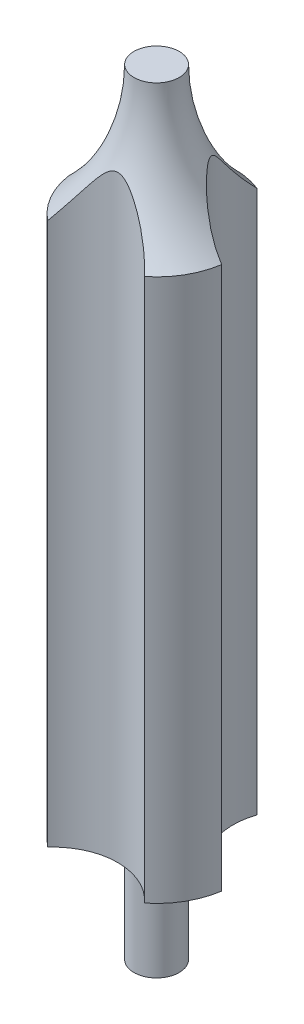
SolidWorks part; units mm, degrees
ref_plane "Спереди" through (0, 0, 0) normal (0, 0, 1) x (1, 0, 0)
ref_plane "Сверху" through (0, 0, 0) normal (0, 1, 0) x (1, 0, 0)
ref_plane "Справа" through (0, 0, 0) normal (1, 0, 0) x (0, 0, -1)
sketch "Эскиз1" plane through (0, 0, 0) normal (0, 0, 1) x (1, 0, 0)
  line L0 (0, 18.1736) -> (0, -11.8264)
  line L1 (0, 18.1736) -> (-0.875, 18.1736)
  line L2 (-3, 13.1736) -> (0, 13.1736)
  line L3 (-3, 13.1736) -> (-3, -7.8264)
  line L4 (-3, -7.8264) -> (-0.875, -7.8264)
  line L5 (-0.875, -7.8264) -> (-0.875, -11.8264)
  line L6 (-0.875, -11.8264) -> (0, -11.8264)
  arc A1 (-3, 13.1736) -> (-0.875, 18.1736) centre (-7.875, 18.1971) ccw
  point P8 (0, -11.7055)
  point P12 (0, 0)
  point P14 (-0.875, 18.1325)
  dimension "D2" = 26
  dimension "D5" = 7
  dimension "D1" = 0.875
  dimension "D3" = 5
  dimension "D4" = 3
  dimension "D6" = 30
revolve "Повернуть1" add sketch "Эскиз1" angle 360 about L0
sketch "Эскиз2" plane through (0, 18.1736, 0) normal (0, 1, 0) x (1, 0, 0)
  line L0 (0, -4) -> (0, 0) construction
  line L1 (0, 0) -> (-3.4641, 2) construction
  line L2 (3.4641, 2) -> (0, 0) construction
  circle A0 centre (-3.4641, 2) radius 2.5
  circle A1 centre (3.4641, 2) radius 2.5
  circle A2 centre (0, -4) radius 2.5
  circle A3 centre (0, 0) radius 1.5
  point P6 (-1.299, 0.75)
  point P9 (1.299, 0.75)
  point P10 (0, -1.5)
  point P12 (0, 0)
  point P13 (0, 0)
  dimension "D3" = 5
  dimension "D4" = 5
  dimension "D5" = 5
  dimension "D6" = 3
  dimension "D1" = 120
  dimension "D2" = 120
extrude "Вырез-Вытянуть1" cut sketch "Эскиз2" against normal through all both and the other way through all contours A0 | A1 | A2
sketch "Эскиз3" plane through (0, -11.8264, 0) normal (0, -1, 0) x (1, 0, 0)
  circle A0 centre (0, 0) radius 0.5
  dimension "D1" = 1
extrude "Вырез-Вытянуть2" cut sketch "Эскиз3" against normal blind 2
chamfer "Фаска1" distance 0.49 angle 45 1 edges at (0.5, -9.8264, 0)
